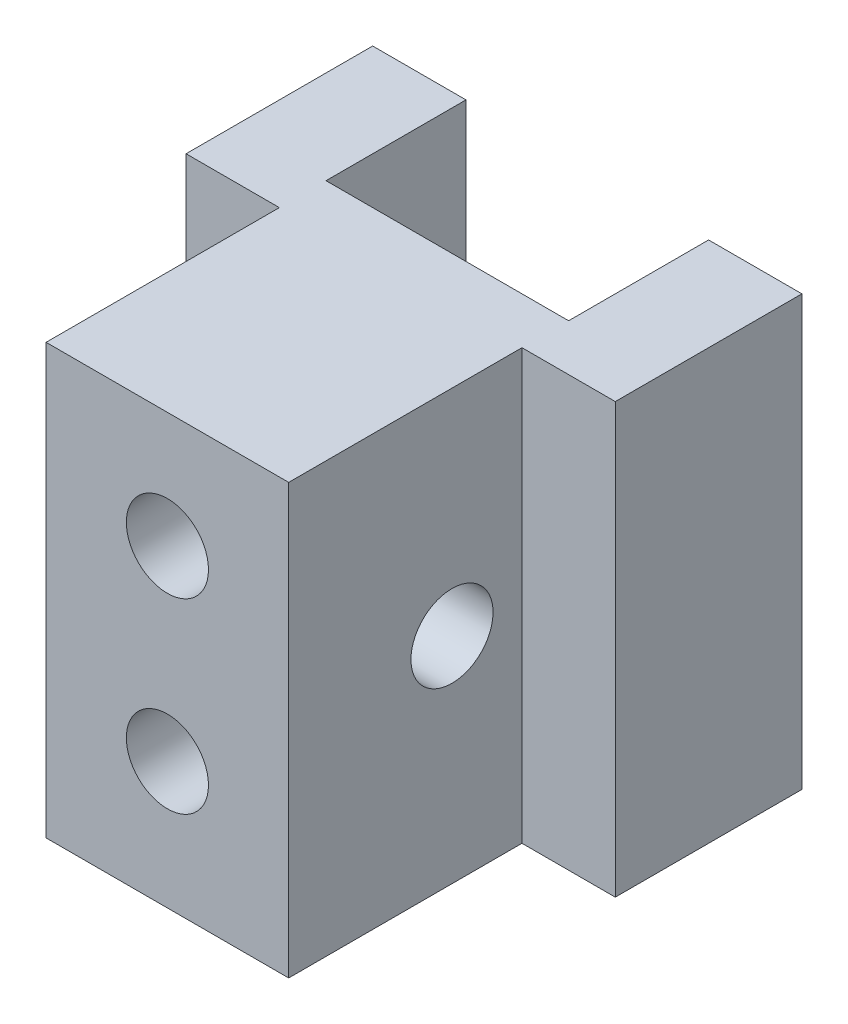
SolidWorks part; units mm, degrees
ref_plane "Front Plane" through (0, 0, 0) normal (0, 0, 1) x (1, 0, 0)
ref_plane "Top Plane" through (0, 0, 0) normal (0, 1, 0) x (1, 0, 0)
ref_plane "Right Plane" through (0, 0, 0) normal (1, 0, 0) x (0, 0, -1)
sketch "Sketch2" plane through (0, 0, 0) normal (0, 0, 1) x (1, 0, 0)
  line L0 (-33.5, -128.1) -> (-33.5, -205.8) construction
  line L1 (-20.5, -128.1) -> (-33.5, -128.1)
  line L2 (-20.5, -128.1) -> (-20.5, -151.1)
  line L3 (-20.5, -151.1) -> (-33.5, -151.1)
  line L4 (-33.5, -128.1) -> (-33.5, -151.1)
  circle A0 centre (-27, -144.3) radius 2.2 construction
  circle A1 centre (-27, -144.3) radius 2.2
  circle A2 centre (-27, -134.3) radius 2.2 construction
  circle A3 centre (-27, -134.3) radius 2.2
  dimension "D1" = 23
extrude "Boss-Extrude1" add sketch "Sketch2" along normal blind 10
sketch "Sketch5" plane through (0, 0, 0) normal (0, 0, -1) x (-1, 0, 0)
  line L2 (15.5, -151.1) -> (15.5, -128.1)
  line L3 (15.5, -151.1) -> (15.5, -128.1)
  line L4 (33.5, -128.1) -> (33.5, -151.1) construction
  line L5 (38.5, -128.1) -> (38.5, -151.1)
  line L6 (38.5, -128.1) -> (38.5, -151.1)
  line L7 (20.5, -151.1) -> (20.5, -128.1) construction
  line L8 (33.5, -128.1) -> (33.5, -151.1)
  line L9 (20.5, -151.1) -> (20.5, -128.1)
  line L10 (33.5, -151.1) -> (38.5, -151.1)
  line L11 (38.5, -128.1) -> (33.5, -128.1)
  line L12 (20.5, -128.1) -> (15.5, -128.1)
  line L13 (15.5, -151.1) -> (20.5, -151.1)
  dimension "D1" = 5
  dimension "D2" = 5
extrude "Boss-Extrude2" add sketch "Sketch5" against normal blind 2.5
sketch "Sketch6" plane through (0, 0, 0) normal (0, 0, -1) x (-1, 0, 0)
  line L0 (20.5, -128.1) -> (20.5, -151.1)
  line L1 (33.5, -151.1) -> (33.5, -128.1)
  line L4 (38.5, -128.1) -> (15.5, -128.1)
  line L5 (15.5, -128.1) -> (15.5, -151.1)
  line L6 (15.5, -151.1) -> (38.5, -151.1)
  line L7 (38.5, -151.1) -> (38.5, -128.1)
  line L8 (38.5, -128.1) -> (15.5, -128.1)
  line L9 (15.5, -128.1) -> (15.5, -151.1)
  line L10 (15.5, -151.1) -> (38.5, -151.1)
  line L11 (38.5, -151.1) -> (38.5, -128.1)
  line M6 (38.5, -128.1) -> (15.5, -128.1)
  line M7 (15.5, -128.1) -> (15.5, -151.1)
  line M8 (15.5, -151.1) -> (38.5, -151.1)
  line M9 (38.5, -151.1) -> (38.5, -128.1)
  dimension "D1" = 0
  dimension "D2" = 5
  dimension "D3" = 5
extrude "Boss-Extrude3" add sketch "Sketch6" along normal blind 7.5 contours L0 M6 M7 M8 | L1 M8 M9 M6
sketch "Sketch7" plane through (-20.5, 0, 0) normal (1, 0, 0) x (0, 0, -1)
  line L0 (-6.25, -151.1) -> (-6.25, -128.1)
  line L1 (-10, -151.1) -> (-2.5, -151.1) construction
  line L2 (-10, -128.1) -> (-2.5, -128.1) construction
  circle A0 centre (-6.25, -139.6) radius 2.2
  dimension "D1" = 4.4
extrude "Cut-Extrude2" cut sketch "Sketch7" against normal through all contours L0 A0 | L0 A0
sketch "Sketch8" plane through (0, 0, 10) normal (0, 0, 1) x (1, 0, 0)
  line L4 (-20.5, -151.1) -> (-20.5, -128.1)
  line L5 (-20.5, -128.1) -> (-33.5, -128.1)
  line L6 (-33.5, -128.1) -> (-33.5, -151.1)
  line L7 (-33.5, -151.1) -> (-20.5, -151.1)
  line L8 (-20.5, -151.1) -> (-20.5, -128.1)
  line L9 (-20.5, -128.1) -> (-33.5, -128.1)
  line L10 (-33.5, -128.1) -> (-33.5, -151.1)
  line L11 (-33.5, -151.1) -> (-20.5, -151.1)
  circle A4 centre (-27, -134.3) radius 2.2 construction
  circle A5 centre (-27, -144.3) radius 2.2 construction
  circle A6 centre (-27, -134.3) radius 2.2
  circle A7 centre (-27, -144.3) radius 2.2
  dimension "D1" = 0
extrude "Boss-Extrude4" add sketch "Sketch8" along normal blind 5
